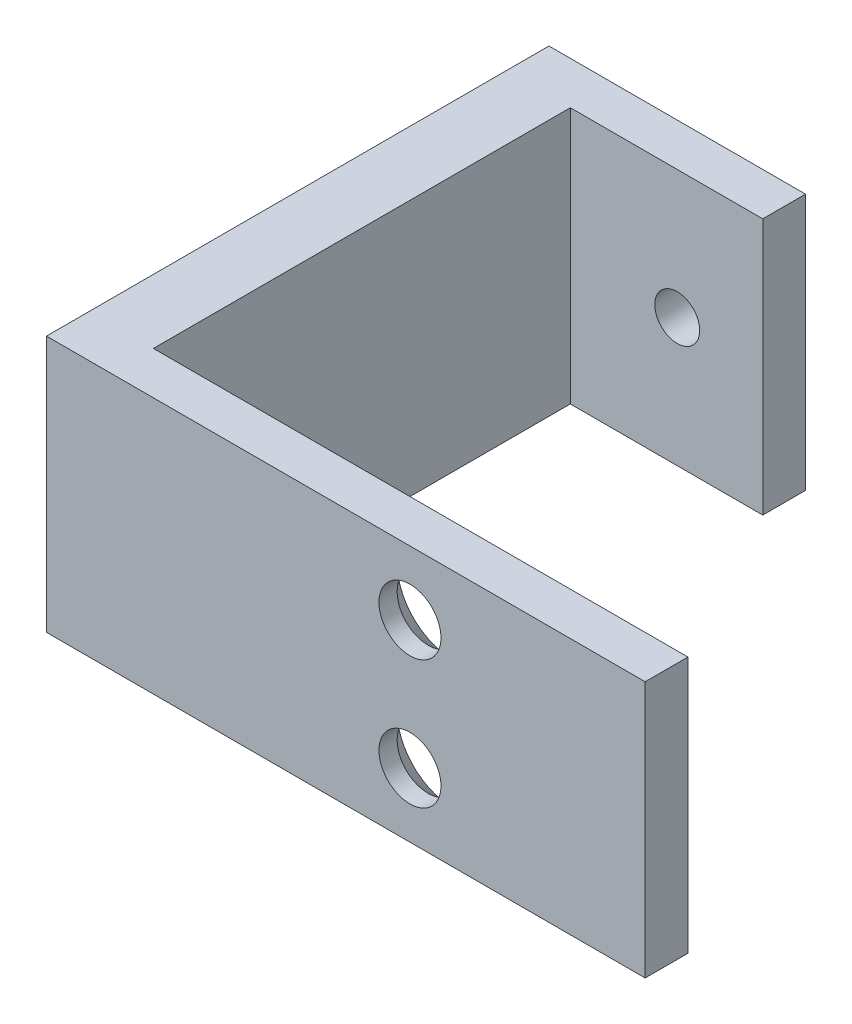
SolidWorks part; units mm, degrees
ref_plane "Front Plane" through (0, 0, 0) normal (0, 0, 1) x (1, 0, 0)
ref_plane "Top Plane" through (0, 0, 0) normal (0, 1, 0) x (1, 0, 0)
ref_plane "Right Plane" through (0, 0, 0) normal (1, 0, 0) x (0, 0, -1)
sketch "Sketch1" plane through (0, 0, 0) normal (0, 0, 1) x (1, 0, 0)
  line L1 (-44, -26) -> (-32, -26)
  line L2 (-44, -26) -> (-44, -14)
  line L3 (-44, -14) -> (-32, -14)
  line L4 (-32, -26) -> (-32, -14)
  circle A0 centre (-36, -20) radius 1.05
extrude "Link_Eye_Shelf" add sketch "Sketch1" along normal blind 2 from offset 23.5
sketch "Sketch2" plane through (0, 0, 0) normal (0, 0, 1) x (1, 0, 0)
  line L1 (-44, -26) -> (-41, -26)
  line L2 (-44, -26) -> (-44, -14)
  line L3 (-44, -14) -> (-41, -14)
  line L4 (-41, -26) -> (-41, -14)
extrude "Outboard_Web" add sketch "Sketch2" along normal blind 21.5 from offset 22.5
sketch "Sketch3" plane through (0, 0, 0) normal (0, 0, 1) x (1, 0, 0)
  line L1 (-44, -26) -> (-16, -26)
  line L2 (-44, -26) -> (-44, -14)
  line L3 (-44, -14) -> (-16, -14)
  line L4 (-16, -26) -> (-16, -14)
extrude "Carriage_Plate_Foot" add sketch "Sketch3" along normal blind 2 from offset 2
sketch "Sketch4" plane through (0, 0, -2) normal (0, 0, -1) x (-1, 0, 0)
  circle A0 centre (20, -23) radius 1.45
  circle A1 centre (20, -17) radius 1.45
sketch "Sketch5" plane through (0, 0, -2) normal (0, 0, -1) x (-1, 0, 0)
  circle A0 centre (20, -23) radius 2.6
  circle A1 centre (20, -17) radius 2.6
sketch "Sketch6" plane through (0, 0, -2) normal (0, 0, -1) x (-1, 0, 0)
  circle A0 centre (27, -23) radius 1.45
  circle A1 centre (27, -17) radius 1.45
extrude "YTab_D2p9" cut sketch "Sketch6" against normal blind 2.01
sketch "Sketch7" plane through (0, 0, -2) normal (0, 0, -1) x (-1, 0, 0)
  circle A0 centre (27, -23) radius 2.6
  circle A1 centre (27, -17) radius 2.6
extrude "YTab_CSK_D5p2" cut sketch "Sketch7" against normal blind 1.15 draft 45
